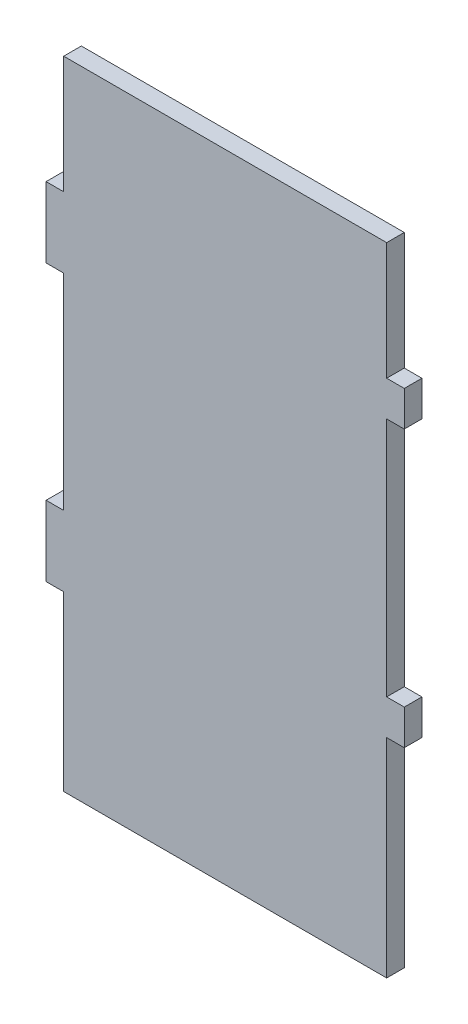
SolidWorks part; units mm, degrees
ref_plane "Přední rovina" through (0, 0, 0) normal (0, 0, 1) x (1, 0, 0)
ref_plane "Horní rovina" through (0, 0, 0) normal (0, 1, 0) x (1, 0, 0)
ref_plane "Pravá rovina" through (0, 0, 0) normal (1, 0, 0) x (0, 0, -1)
sketch "Skica1" plane through (0, 0, 0) normal (0, 0, 1) x (1, 0, 0)
  line L0 (0, 0) -> (55, 0)
  line L1 (0, 0) -> (0, -20)
  line L2 (55, 0) -> (55, -20)
  line L3 (0, -108.46) -> (55, -108.46)
  line L5 (0, -20) -> (-3, -20)
  line L7 (0, -32) -> (-3, -32)
  line L8 (-3, -20) -> (-3, -32)
  line L9 (0, -67) -> (-3, -67)
  line L11 (0, -79) -> (-3, -79)
  line L12 (-3, -67) -> (-3, -79)
  line L13 (55, -73) -> (58, -73)
  line L14 (58, -67) -> (58, -73)
  line L15 (55, -67) -> (58, -67)
  line L16 (55, -20) -> (58, -20)
  line L17 (55, -26) -> (58, -26)
  line L18 (58, -20) -> (58, -26)
  line L19 (55, -73) -> (55, -108.46)
  line L20 (55, -26) -> (55, -67)
  line L21 (0, -32) -> (0, -67)
  line L22 (0, -79) -> (0, -108.46)
  dimension "D1" = 55
  dimension "D2" = 108.46
  dimension "D3" = 3
  dimension "D4" = 3
  dimension "D5" = 12
  dimension "D6" = 12
  dimension "D7" = 20
  dimension "D8" = 35
  dimension "D9" = 6
  dimension "D10" = 20
  dimension "D11" = 3
  dimension "D12" = 6
  dimension "D13" = 41
  dimension "D14" = 3
extrude "Přidat vysunutím1" add sketch "Skica1" along normal blind 3
